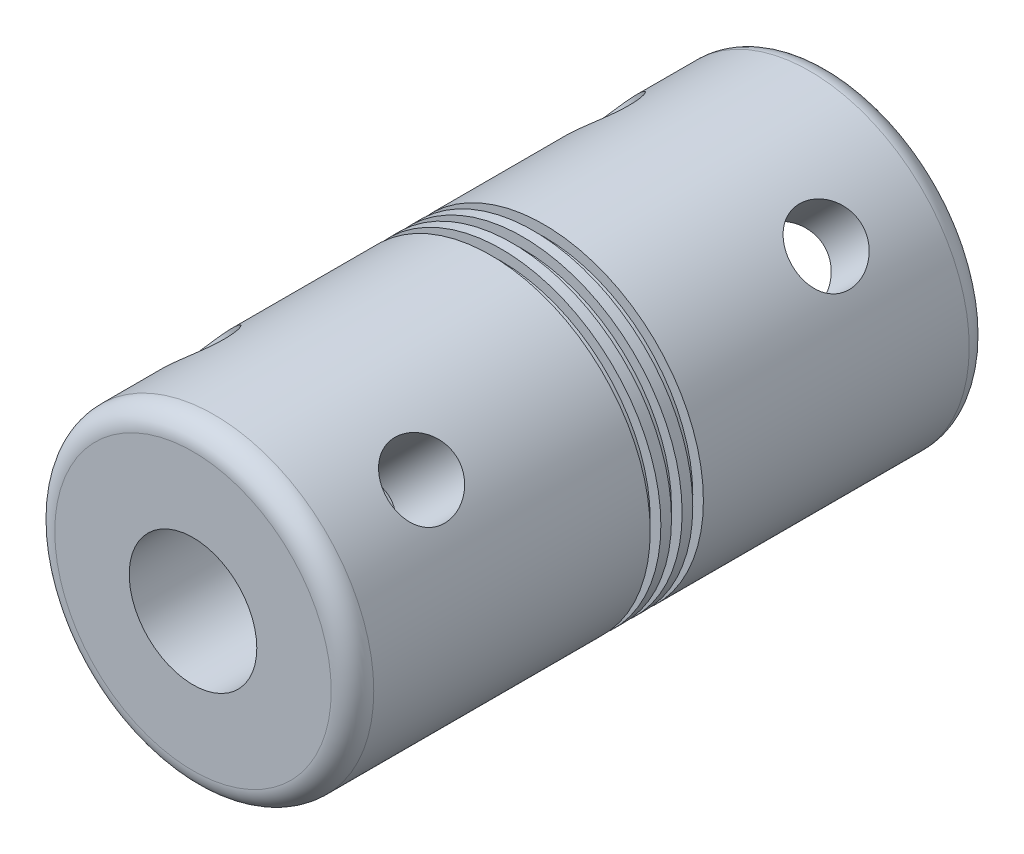
SolidWorks part; units mm, degrees
ref_plane "Front Plane" through (0, 0, 0) normal (0, 0, 1) x (1, 0, 0)
ref_plane "Top Plane" through (0, 0, 0) normal (0, 1, 0) x (1, 0, 0)
ref_plane "Right Plane" through (0, 0, 0) normal (1, 0, 0) x (0, 0, -1)
sketch "Sketch2" plane through (0, 0, 0) normal (0, 0, 1) x (1, 0, 0)
  circle A0 centre (0, 0) radius 7.5
  dimension "D1" = 15
extrude "Boss-Extrude1" add sketch "Sketch2" along normal mid plane 30
sketch "Sketch3" plane through (0, 0, 15) normal (0, 0, 1) x (1, 0, 0)
  circle A0 centre (0, 0) radius 3
  dimension "D1" = 6
extrude "Cut-Extrude1" cut sketch "Sketch3" against normal blind 15
sketch "Sketch4" plane through (0, 0, -15) normal (0, 0, -1) x (-1, 0, 0)
  circle A0 centre (0, 0) radius 5
  dimension "D1" = 10
extrude "Cut-Extrude2" cut sketch "Sketch4" against normal blind 15
sketch "Sketch5" plane through (0, 0, 0) normal (0, 0, 1) x (1, 0, 0)
  circle A0 centre (0, 0) radius 7
  circle A1 centre (0, 0) radius 7.5
  dimension "D1" = 14
extrude "Cut-Extrude3" cut sketch "Sketch5" against normal blind 0.5
pattern_linear "LPattern1" count 2 spacing 1 along (0, 0, -1) of "Cut-Extrude3"
pattern_linear "LPattern2" count 2 spacing 1 along (0, 0, 1) of "Cut-Extrude3"
ref_plane "Plane1" through (-5.3033, 5.3033, 0) normal (-0.7071, 0.7071, 0) x (0, 0, -1)
hole_wizard "M4 Tapped Hole1" positions "Sketch8" profile "Sketch9" tap size "M4" standard "ISO"
sketch "Sketch8" plane through (-5.3033, 5.3033, 0) normal (-0.7071, 0.7071, 0) x (0, 0, -1)
  point P0 (9.5111, 0)
sketch "Sketch9" plane through (-5.3033, 5.3033, -9.5111) normal (0, 0, 1) x (-0.7071, -0.7071, 0)
  line L0 (0, 0) -> (0, 6.9914)
  line L1 (0, 6.9914) -> (1.65, 6)
  line L2 (1.65, 6) -> (1.65, 0)
  line L5 (1.65, 0) -> (0, 0)
  line L10 (0, 6.9914) -> (-1.65, 6) construction
  line L11 (0, -6.35) -> (0, 107.95) construction
  dimension "Tap Drill Dia." = 3.3
  dimension "Tap Drill Depth" = 6
  dimension "Drill Angle" = 118
cosmetic thread "Hole Thread1" parameters "D1"=2.78, "D2"=4
mirror "Mirror1" about plane through (0, 0, 0) normal (1, 0, 0) of "M4 Tapped Hole1"
cosmetic thread "Hole Thread2" parameters "D1"=2.78, "D2"=4
mirror "Mirror2" about plane through (0, 0, 0) normal (0, 0, 1) of "Mirror1", "M4 Tapped Hole1"
cosmetic thread "Hole Thread3" parameters "D1"=2.78, "D2"=4
cosmetic thread "Hole Thread4" parameters "D1"=2.78, "D2"=4
fillet "Fillet1" radius 1 2 edges at (7.5, 0, 15) (7.5, 0, -15)
